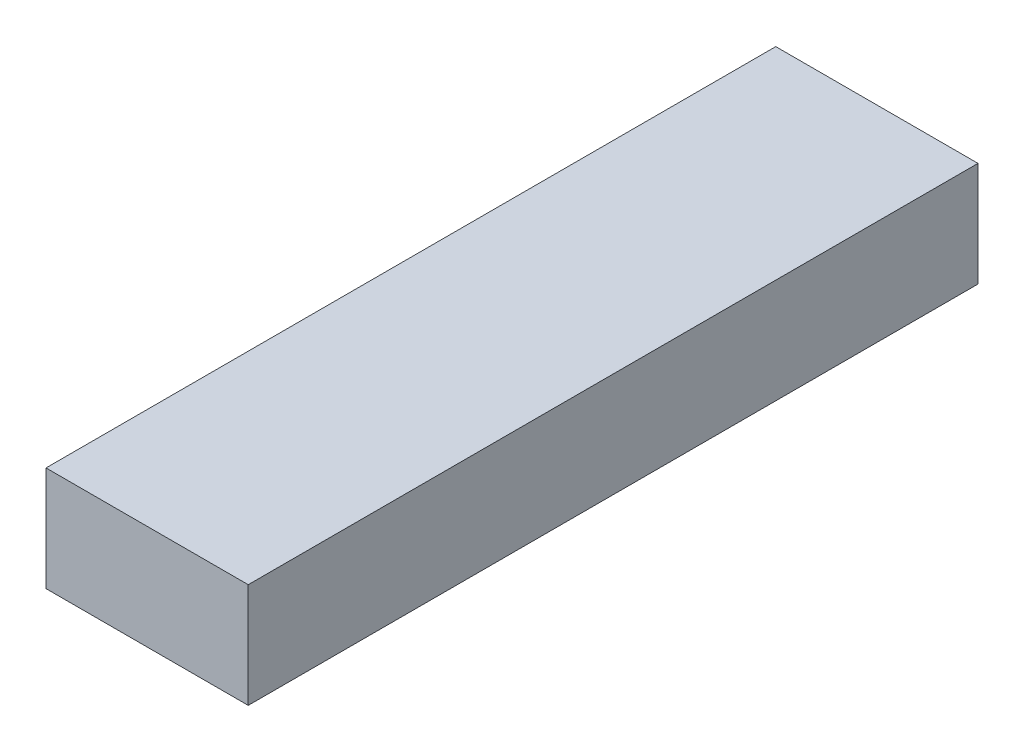
SolidWorks part; units mm, degrees
ref_plane "Front Plane" through (0, 0, 0) normal (0, 0, 1) x (1, 0, 0)
ref_plane "Top Plane" through (0, 0, 0) normal (0, 1, 0) x (1, 0, 0)
ref_plane "Right Plane" through (0, 0, 0) normal (1, 0, 0) x (0, 0, -1)
sketch "Sketch1" plane through (0, 0, 0) normal (0, 1, 0) x (1, 0, 0)
  line L1 (-19.3451, 33.5495) -> (0, 33.5495)
  line L2 (-19.3451, 33.5495) -> (-19.3451, -36.2551)
  line L3 (-19.3451, -36.2551) -> (0, -36.2551)
  line L4 (0, 33.5495) -> (0, -36.2551)
extrude "Boss-Extrude1" add sketch "Sketch1" along normal blind 10
scale "Scale1" scale about centroid uniform scaling yes scale factor 0.7
